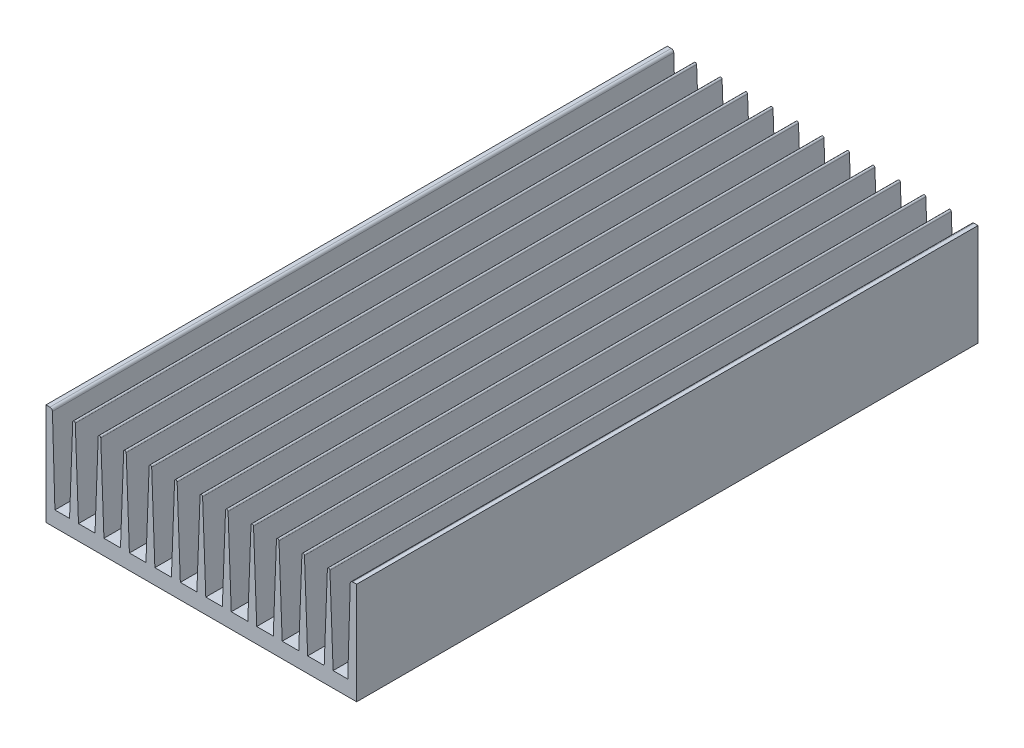
SolidWorks part; units mm, degrees
ref_plane "Спереди" through (0, 0, 0) normal (0, 0, 1) x (1, 0, 0)
ref_plane "Сверху" through (0, 0, 0) normal (0, 1, 0) x (1, 0, 0)
ref_plane "Справа" through (0, 0, 0) normal (1, 0, 0) x (0, 0, -1)
sketch "Эскиз1" plane through (0, 0, 0) normal (0, 0, 1) x (1, 0, 0)
  line L0 (0, 40) -> (1.529, 40)
  line L1 (0, 0) -> (122, 0)
  line L2 (2.5285, 39.0294) -> (3.5, 6)
  line L3 (0, 40) -> (0, 0)
  line L4 (122, 40) -> (122, 0)
  line L5 (61, 63.7127) -> (61, -22.2582) construction
  line L8 (122, 40) -> (120.471, 40)
  line L9 (119.4715, 39.0294) -> (118.5, 6)
  line L10 (3.5, 6) -> (118.5, 6)
  arc A0 (1.529, 40) -> (2.5285, 39.0294) centre (1.529, 39) cw
  arc A2 (120.471, 40) -> (119.4715, 39.0294) centre (120.471, 39) ccw
  point P18 (119.5, 40)
  dimension "D9" = 1
  dimension "D1" = 122
  dimension "D2" = 6
  dimension "D3" = 40
  dimension "D4" = 3.5
  dimension "D7" = 2.5
extrude "Вытянуть1" add sketch "Эскиз1" along normal blind 244
sketch "Эскиз2" plane through (0, 0, 244) normal (0, 0, 1) x (1, 0, 0)
  line L0 (118.5, 6) -> (3.5, 6) construction
  line L1 (10.5, 39.5) -> (9.25, 6)
  line L2 (11, 39.5) -> (11, 22.5548) construction
  line L3 (11.5, 39.5) -> (12.75, 6)
  line L4 (9.25, 6) -> (12.75, 6)
  line L6 (0, 40) -> (0, 0) construction
  arc A0 (10.5, 39.5) -> (11.5, 39.5) centre (11, 39.5) cw
  dimension "D1" = 34
  dimension "D3" = 0.5
  dimension "D2" = 3.5
  dimension "D4" = 11
  dimension "D5" = 1
extrude "Вытянуть3" add sketch "Эскиз2" against normal blind 244
pattern_curve "Кривая1" of "Вытянуть3" along edge at (61, 0, 0) parameters "D1"=11, "D3"=10, "D2"=1, "D4"=50
sketch "Эскиз3" plane through (0, 0, 0) normal (0, -1, 0) x (1, 0, 0)
  line L0 (-14.0506, 236) -> (137.5079, 236) construction
  line L1 (0, 244) -> (122, 244) construction
  line L2 (0, 244) -> (0, 0) construction
  line L3 (-46.7511, 122) -> (151.4312, 122) construction
  line L4 (0, 0) -> (122, 0) construction
  circle A0 centre (26, 236) radius 2.25
  circle A1 centre (96, 236) radius 2.25
  circle A2 centre (96, 8) radius 2.25
  circle A3 centre (26, 8) radius 2.25
  dimension "D2" = 70
  dimension "D4" = 4.5
  dimension "D1" = 8
  dimension "D3" = 26
extrude "Вырез-Вытянуть1" cut sketch "Эскиз3" against normal blind 6
sketch "Эскиз4" plane through (-5.7236, 0, -26.359) normal (0, -1, 0) x (1, 0, 0)
  line L0 (90.2236, 189.359) -> (90.2236, 64.1478) construction
  line L1 (57.2236, 147.359) -> (57.2236, 49.359) construction
  line L2 (5.7236, 26.359) -> (127.7236, 26.359) construction
  line L3 (57.2236, 147.359) -> (57.2236, 128.359) construction
  line L4 (75.7236, 72.359) -> (75.7236, 46.359) construction
  line L5 (127.7236, 270.359) -> (127.7236, 26.359) construction
  line L6 (5.7236, 270.359) -> (5.7236, 26.359) construction
  circle A0 centre (75.7236, 72.359) radius 1.25
  circle A1 centre (90.2236, 189.359) radius 1.6
  circle A2 centre (90.2236, 49.359) radius 1.6
  circle A3 centre (57.2236, 147.359) radius 1.6
  circle A4 centre (57.2236, 128.359) radius 1.6
  circle A5 centre (75.7236, 46.359) radius 1.25
  circle A6 centre (57.2236, 116.359) radius 1.6
  circle A7 centre (57.2236, 69.859) radius 1.6
  dimension "D2" = 2.5
  dimension "D6" = 121
  dimension "D7" = 70
  dimension "D9" = 23
  dimension "D10" = 26
  dimension "D12" = 46.5
  dimension "D14" = 3.2
  dimension "D4" = 20
  dimension "D5" = 102
  dimension "D3" = 2.5
  dimension "D13" = 12
  dimension "D1" = 140
  dimension "D8" = 37.5
  dimension "D11" = 70.5
extrude "Вырез-Вытянуть2" cut sketch "Эскиз4" against normal blind 5.5
cosmetic thread "Условное изображение резьбы11" parameters "D2"=4
cosmetic thread "Условное изображение резьбы12" parameters "D2"=4
cosmetic thread "Условное изображение резьбы13" parameters "D2"=4
cosmetic thread "Условное изображение резьбы14" parameters "D2"=4
cosmetic thread "Условное изображение резьбы19" parameters "D2"=3
cosmetic thread "Условное изображение резьбы20" parameters "D2"=3
cosmetic thread "Условное изображение резьбы21"
cosmetic thread "Условное изображение резьбы22"
sketch "Эскиз5" plane through (128.3242, 0, 423.7759) normal (0, -1, 0) x (-1, 0, 0)
  line L0 (56.3242, 222.2759) -> (24.2196, 222.2759) construction
  line L1 (51.3242, 197.71) -> (51.3242, 229.3314) construction
  line L2 (6.3242, 179.7759) -> (6.3242, 423.7759) construction
  line L3 (128.3242, 179.7759) -> (6.3242, 179.7759) construction
  line L4 (81.3242, 239.7759) -> (81.3242, 286.7846) construction
  circle A0 centre (81.3242, 273.7759) radius 2.1
  circle A1 centre (21.3242, 239.7759) radius 1.6
  circle A2 centre (81.3242, 239.7759) radius 1.6
  circle A4 centre (81.3242, 204.7759) radius 1.6
  circle A5 centre (21.3242, 204.7759) radius 1.6
  dimension "D1" = 4.2
  dimension "D3" = 45
  dimension "D4" = 42.5
  dimension "D6" = 94
  dimension "D8" = 60
  dimension "D2" = 3.2
  dimension "D9" = 17.5
extrude "Вырез-Вытянуть3" cut sketch "Эскиз5" against normal blind 6
cosmetic thread "Условное изображение резьбы7" parameters "D2"=5
cosmetic thread "Условное изображение резьбы10" parameters "D2"=5
cosmetic thread "Условное изображение резьбы15" parameters "D2"=4
cosmetic thread "Условное изображение резьбы16" parameters "D2"=4
cosmetic thread "Условное изображение резьбы17" parameters "D2"=4
cosmetic thread "Условное изображение резьбы18" parameters "D2"=4
